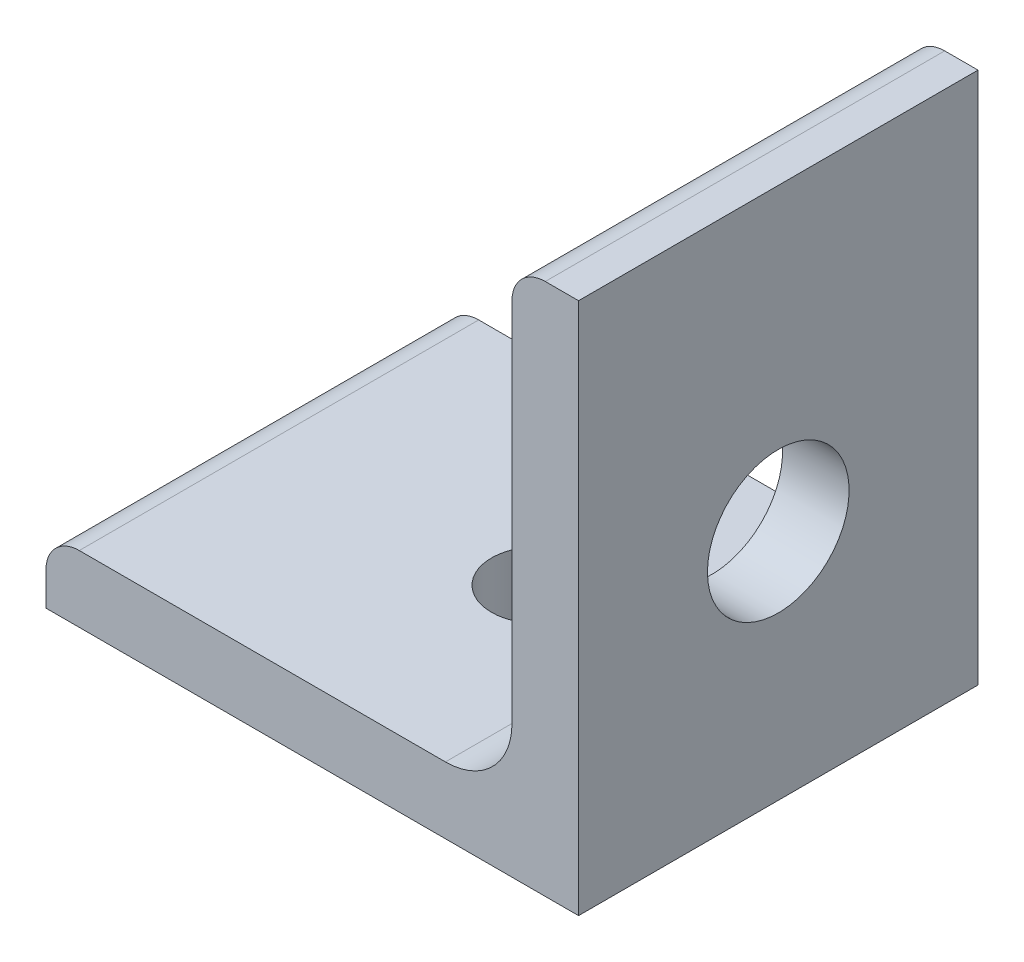
SolidWorks part; units mm, degrees
ref_plane "Front Plane" through (0, 0, 0) normal (0, 0, 1) x (1, 0, 0)
ref_plane "Top Plane" through (0, 0, 0) normal (0, 1, 0) x (1, 0, 0)
ref_plane "Right Plane" through (0, 0, 0) normal (1, 0, 0) x (0, 0, -1)
sketch "Sketch2" plane through (0, 0, 0) normal (0, 0, 1) x (1, 0, 0)
  line L0 (-12.7, 0) -> (12.7, 0)
  line L1 (12.7, 0) -> (12.7, 25.4)
  line L2 (12.7, 25.4) -> (9.525, 25.4) construction
  line L3 (9.525, 23.8125) -> (9.525, 6.35)
  line L4 (6.35, 3.175) -> (-11.1125, 3.175)
  line L5 (-12.7, 0) -> (-12.7, 3.175) construction
  line L6 (11.1125, 25.4) -> (12.7, 25.4)
  line L7 (-12.7, 1.5875) -> (-12.7, 0)
  arc A0 (9.525, 23.8125) -> (11.1125, 25.4) centre (11.1125, 23.8125) cw
  arc A1 (-12.7, 1.5875) -> (-11.1125, 3.175) centre (-11.1125, 1.5875) cw
  arc A2 (9.525, 6.35) -> (6.35, 3.175) centre (6.35, 6.35) cw
  dimension "Inside Radius" = 3.175
  dimension "Vert" = 25.4
  dimension "Horz" = 25.4
  dimension "Thickness" = 3.175
extrude "Boss-Extrude1" add sketch "Sketch2" along normal mid plane 19.05
sketch "Break Locations" plane through (0, 0, 0) normal (1, 0, 0) x (0, 0, -1)
  line L1 (-9.525, 0) -> (-9.525, 25.4) construction
  line L2 (9.525, 0) -> (9.525, 25.4) construction
  point P0 (12.065, 0)
  point P1 (-12.065, 0)
  dimension "D1" = 21.59
  dimension "D2" = 21.59
ref_plane "Contact Plane 1" through (0, 3.175, 0) normal (0, 1, 0) x (1, 0, 0)
ref_plane "Contact Plane 2" through (9.525, 0, 0) normal (-1, 0, 0) x (0, 0, 1)
sketch "Sketch3" plane through (9.525, 0, 0) normal (-1, 0, 0) x (0, 0, 1)
  line L0 (9.525, 23.8125) -> (-9.525, 23.8125) construction
  line L1 (-9.525, 23.8125) -> (-9.525, 6.35) construction
  point P0 (0, 15.0813)
  point P3 (0, 23.8125)
  point P6 (-9.525, 15.0813)
hole_wizard "1/4 Clearance Hole1" positions "Sketch6" profile "Sketch8" hole size "1/4" standard "ANSI Inch" end condition through all
sketch "Sketch6" plane through (9.525, 0, 0) normal (-1, 0, 0) x (0, 0, 1)
  line L1 (9.525, 23.8125) -> (-9.525, 23.8125) construction
  line L2 (9.525, 6.35) -> (-9.525, 6.35) construction
  point P0 (0, 11.1166)
  point P6 (0, 0)
  point P9 (0, 23.8125)
  dimension "D1" = 4.7666
sketch "Sketch8" plane through (9.525, 11.1166, 0) normal (0, 1, 0) x (0, 0, 1)
  line L0 (0, 0) -> (0, 3.175)
  line L1 (0, 3.175) -> (3.3782, 3.175)
  line L2 (3.3782, 3.175) -> (3.3782, 0)
  line L5 (3.3782, 0) -> (0, 0)
  line L11 (0, -6.35) -> (0, 107.95) construction
  dimension "Thru Hole Dia." = 6.7564
  dimension "Thru Hole Depth" = 3.175
sketch "Sketch9" plane through (0, 3.175, 0) normal (0, 1, 0) x (1, 0, 0)
  line L0 (-11.1125, -9.525) -> (-11.1125, 9.525) construction
  line L1 (6.35, 9.525) -> (-11.1125, 9.525) construction
  point P0 (-2.3812, 0)
  point P1 (0, 0)
  point P4 (-11.1125, 0)
  point P5 (-0.826, 0)
  point P8 (-2.3812, 9.525)
hole_wizard "#8 Clearance Hole1" positions "Sketch10" profile "Sketch11" hole size "#8" standard "ANSI Inch" end condition through all
sketch "Sketch10" plane through (0, 3.175, 0) normal (0, 1, 0) x (1, 0, 0)
  line L1 (-11.1125, -9.525) -> (-11.1125, 9.525) construction
  line L2 (6.35, -9.525) -> (6.35, 9.525) construction
  point P0 (1.27, 0)
  point P3 (0, 0)
  point P4 (0, 0)
  point P10 (-11.1125, 0)
  point P11 (0, 0)
  point P12 (0, 0)
  dimension "D1" = 5.08
sketch "Sketch11" plane through (1.27, 3.175, 0) normal (1, 0, 0) x (0, 0, 1)
  line L0 (0, 0) -> (0, 3.175)
  line L1 (0, 3.175) -> (2.2479, 3.175)
  line L2 (2.2479, 3.175) -> (2.2479, 0)
  line L5 (2.2479, 0) -> (0, 0)
  line L11 (0, -6.35) -> (0, 107.95) construction
  dimension "Thru Hole Dia." = 4.4958
  dimension "Thru Hole Depth" = 3.175
equation "\"D1@Break Locations\"=.85*\"Vert@Sketch2\""
equation "\"D2@Break Locations\"=\"D1@Break Locations\""
